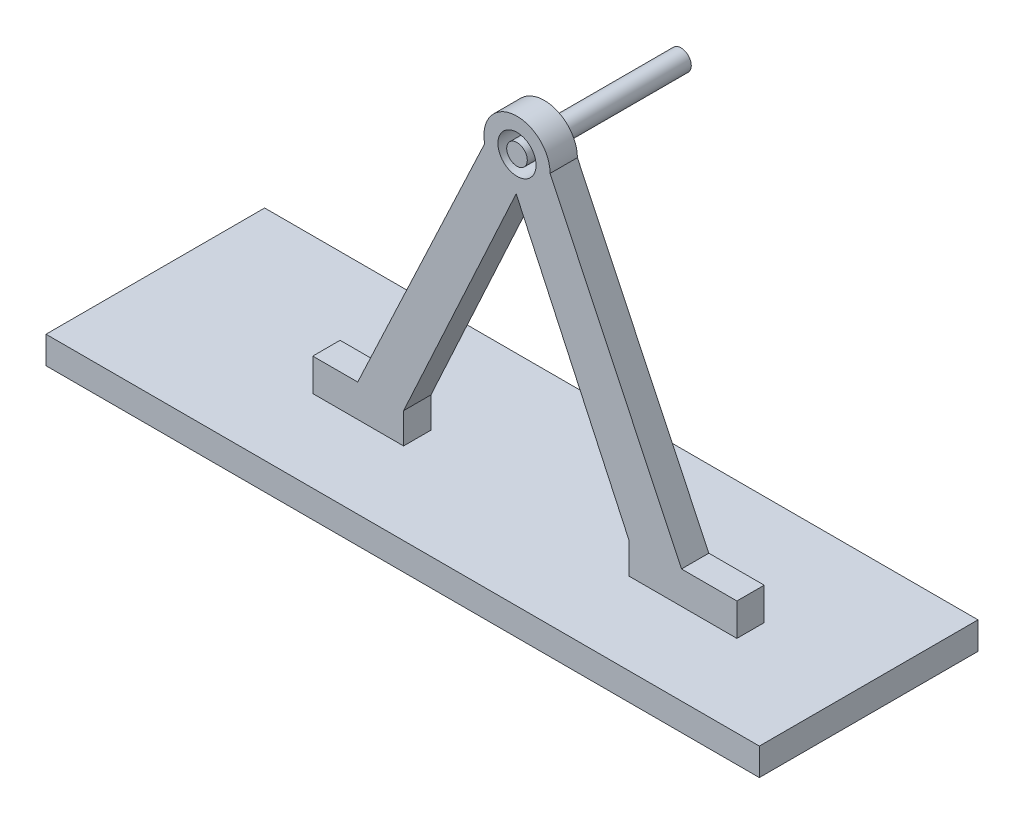
SolidWorks part; units mm, degrees
ref_plane "Front Plane" through (0, 0, 0) normal (0, 0, 1) x (1, 0, 0)
ref_plane "Top Plane" through (0, 0, 0) normal (0, 1, 0) x (1, 0, 0)
ref_plane "Right Plane" through (0, 0, 0) normal (1, 0, 0) x (0, 0, -1)
sketch "Sketch3" plane through (0, 0, 0) normal (0, 1, 0) x (1, 0, 0)
  line L1 (0, 0) -> (132.588, 0)
  line L2 (0, 0) -> (0, 40.64)
  line L3 (0, 40.64) -> (132.588, 40.64)
  line L4 (132.588, 0) -> (132.588, 40.64)
  dimension "D1" = 132.588
  dimension "D2" = 40.64
extrude "Boss-Extrude2" add sketch "Sketch3" along normal blind 5.08
ref_plane "Plane1" through (0, 0, -20.32) normal (0, 0, 1) x (1, 0, 0)
sketch "Sketch4" plane through (0, 0, -20.32) normal (0, 0, 1) x (1, 0, 0)
  line L0 (42.6953, 5.08) -> (34.341, 5.08)
  line L1 (0, 5.08) -> (132.588, 5.08) construction
  line L2 (34.341, 5.08) -> (34.341, 11.1096)
  line L3 (34.341, 11.1096) -> (42.6953, 11.1096)
  line L4 (42.6953, 11.1096) -> (66.294, 61.2646)
  line L5 (78.4486, 62.563) -> (102.8806, 11.1096)
  line L6 (102.8806, 11.1096) -> (113.1745, 11.1096)
  line L7 (113.1745, 11.1096) -> (113.1745, 5.08)
  line L8 (113.1745, 5.08) -> (42.6953, 5.08)
  arc A0 (78.4486, 62.563) -> (66.294, 61.2646) centre (72.3019, 62.563) ccw
  circle A1 centre (72.3019, 62.563) radius 3.5418
extrude "Boss-Extrude3" add sketch "Sketch4" along normal blind 5.08
sketch "Sketch5" plane through (0, 0, -15.24) normal (0, 0, 1) x (1, 0, 0)
  line L0 (72.1506, 56.147) -> (51.2218, 10.7583)
  line L2 (93.1655, 10.7583) -> (72.1506, 56.147)
  line L3 (51.2218, 10.7583) -> (51.2218, 5.08)
  line L4 (0, 5.08) -> (132.588, 5.08) construction
  line L5 (51.2218, 5.08) -> (93.1655, 5.08)
  line L6 (93.1655, 5.08) -> (93.1655, 10.7583)
extrude "Cut-Extrude1" cut sketch "Sketch5" against normal blind 5.08
sketch "Sketch6" plane through (0, 0, -15.24) normal (0, 0, 1) x (1, 0, 0)
  circle A0 centre (72.3019, 62.563) radius 1.9157
extrude "Boss-Extrude4" add sketch "Sketch6" against normal blind 30.48 separate body
